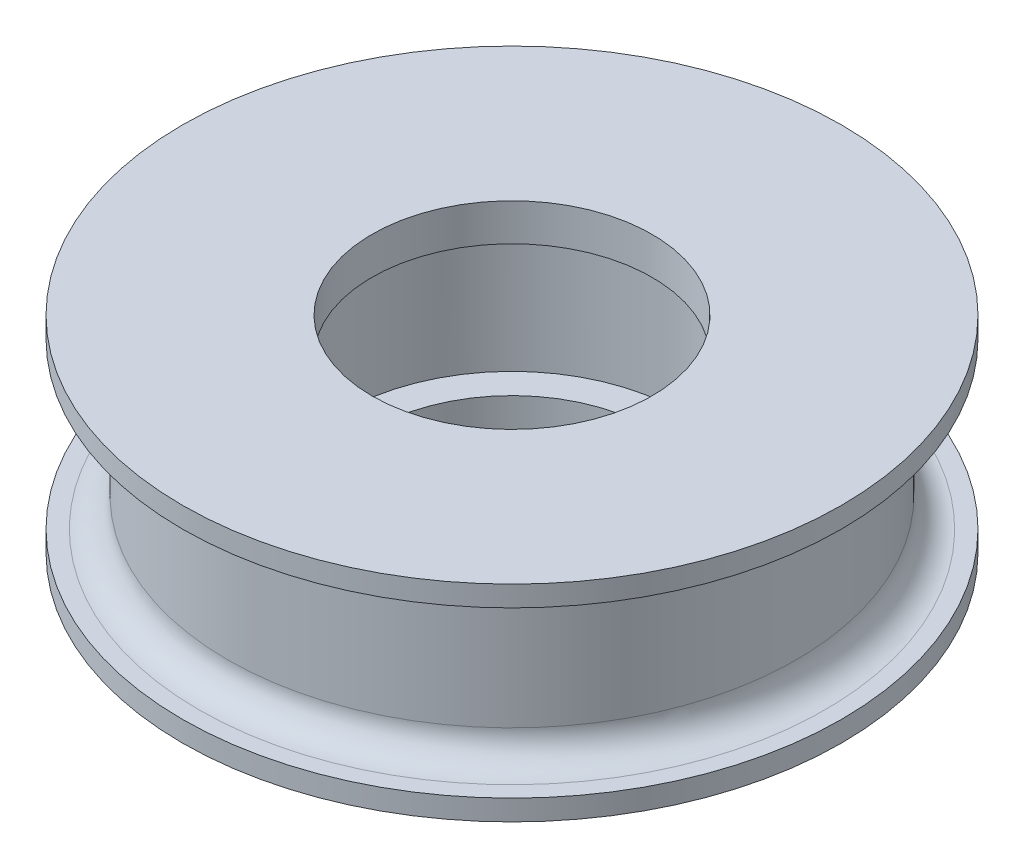
SolidWorks part; units mm, degrees
ref_plane "Front Plane" through (0, 0, 0) normal (0, 0, 1) x (1, 0, 0)
ref_plane "Top Plane" through (0, 0, 0) normal (0, 1, 0) x (1, 0, 0)
ref_plane "Right Plane" through (0, 0, 0) normal (1, 0, 0) x (0, 0, -1)
sketch "Sketch1" plane through (0, 0, 0) normal (0, 1, 0) x (1, 0, 0)
  line L1 (-7.479, 0) -> (-3.7395, -6.477) construction
  line L2 (-3.7395, -6.477) -> (3.7395, -6.477) construction
  line L3 (3.7395, -6.477) -> (7.479, 0) construction
  line L4 (7.479, 0) -> (3.7395, 6.477) construction
  line L5 (3.7395, 6.477) -> (-3.7395, 6.477) construction
  line L6 (-3.7395, 6.477) -> (-7.479, 0) construction
  circle A0 centre (0, 0) radius 6.477 construction
  circle A1 centre (0, 0) radius 25.4
  circle A2 centre (0, 0) radius 13.081
  dimension "pulley_dia" = 50.8
  dimension "D3" = 26.162
extrude "Boss-Extrude1" add sketch "Sketch1" along normal blind 15.875
fillet "Fillet1" [suppressed] radius 0.508
sketch "Sketch6" plane through (0, 15.875, 0) normal (0, 1, 0) x (1, 0, 0)
  line L1 (3.8128, -6.604) -> (7.6256, 0)
  line L2 (7.6256, 0) -> (3.8128, 6.604)
  line L3 (3.8128, 6.604) -> (-3.8128, 6.604)
  line L4 (-3.8128, 6.604) -> (-7.6256, 0)
  line L5 (-7.6256, 0) -> (-3.8128, -6.604)
  line L6 (-3.8128, -6.604) -> (3.8128, -6.604)
  circle A0 centre (0, 0) radius 6.604 construction
  dimension "D1" = 13.208
extrude "Cut-Extrude1" [suppressed] cut sketch "Sketch6" against normal through all
fillet "Fillet2" [suppressed] radius 0.508
sketch "Sketch2" plane through (0, 0, 0) normal (0, 0, 1) x (1, 0, 0)
  line L0 (0, 0) -> (0, 15.875) construction
  line L1 (25.4, 15.875) -> (-25.4, 15.875) construction
  line L2 (25.4, 0) -> (25.4, 15.875) construction
  line L3 (25.4, 14.2875) -> (24.13, 14.2875)
  line L4 (25.4, 14.2875) -> (25.4, 1.5875)
  line L5 (25.4, 1.5875) -> (24.13, 1.5875)
  line L6 (21.9075, 12.065) -> (21.9075, 3.81)
  line L7 (0, 7.9375) -> (21.9075, 7.9375) construction
  arc A0 (24.13, 1.5875) -> (21.9075, 3.81) centre (24.13, 3.81) cw
  arc A1 (21.9075, 12.065) -> (24.13, 14.2875) centre (24.13, 12.065) cw
  point P17 (21.9075, 14.2875)
  dimension "cut_radius" = 2.2225
  dimension "cut_thickness" = 12.7
  dimension "cut_depth" = 3.4925
revolve "Cut-Revolve1" cut sketch "Sketch2" angle 360 about L0
hole_wizard "CBORE for #8 Binding Head Machine Screw1" [suppressed] positions "Sketch4" profile "Sketch5" counterbore size "#8" standard "ANSI Inch"
sketch "Sketch4" plane through (0, 17.145, 0) normal (0, 1, 0) x (1, 0, 0)
  line L0 (0, 0) -> (0, 18.415) construction
  point P0 (0, 18.415)
  dimension "bolt_cir_dia" = 18.415
sketch "Sketch5" plane through (0, 17.145, -18.415) normal (1, 0, 0) x (0, 0, 1)
  line L0 (0, 0) -> (0, 17.145)
  line L1 (0, 17.145) -> (2.2479, 17.145)
  line L3 (2.2479, 17.145) -> (2.2479, 2.667)
  line L4 (2.2479, 2.667) -> (4.7625, 2.667)
  line L5 (4.7625, 2.667) -> (4.7625, 0)
  line L7 (4.7625, 0) -> (0, 0)
  line L11 (0, -6.35) -> (0, 107.95) construction
  dimension "Thru Hole Dia." = 4.4958
  dimension "Thru Hole Depth" = 17.145
  dimension "C'Bore Dia." = 9.525
  dimension "C'Bore Depth" = 2.667
pattern_circular "CirPattern1" [suppressed] count 6 over 360
sketch "Sketch7" plane through (0, 0, 0) normal (0, -1, 0) x (1, 0, 0)
  circle A0 centre (0, 0) radius 15.875
  circle A1 centre (0, 0) radius 10.795
  dimension "D1" = 31.75
  dimension "D2" = 21.59
extrude "Boss-Extrude2" add sketch "Sketch7" against normal blind 2.8702
sketch "Sketch9" plane through (0, 15.875, 0) normal (0, 1, 0) x (1, 0, 0)
  circle A1 centre (0, 0) radius 10.795
  circle A2 centre (0, 0) radius 10.795
  circle A3 centre (0, 0) radius 15.875
  circle A4 centre (0, 0) radius 15.875
  dimension "D1" = 0
  dimension "D2" = 0
extrude "Boss-Extrude5" add sketch "Sketch9" against normal blind 2.8702
sketch "Sketch10" plane through (0, 13.0048, 0) normal (0, -1, 0) x (1, 0, 0)
  circle A0 centre (0, 0) radius 41.7106
extrude "Cut-Extrude2" [suppressed] cut sketch "Sketch10" along normal through all
